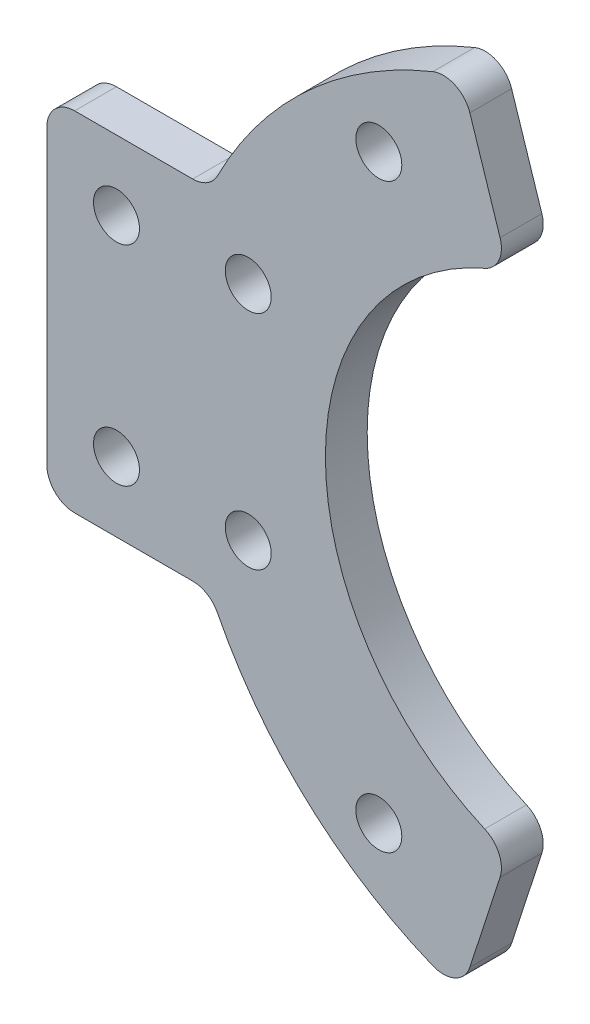
SolidWorks part; units mm, degrees
ref_plane "Front Plane" through (0, 0, 0) normal (0, 0, 1) x (1, 0, 0)
ref_plane "Top Plane" through (0, 0, 0) normal (0, 1, 0) x (1, 0, 0)
ref_plane "Right Plane" through (0, 0, 0) normal (1, 0, 0) x (0, 0, -1)
sketch "Sketch1" plane through (0, 0, 0) normal (0, 0, 1) x (1, 0, 0)
  line L0 (-17.2607, 53.1231) -> (-12.9197, 39.7628)
  line L1 (-12.9197, -39.7628) -> (-17.2607, -53.1231)
  line L2 (-51.6, 0) -> (-68, 0) construction
  line L3 (-68, 15) -> (-68, -15) construction
  line L4 (-57.0526, 25) -> (-74, 25)
  line L5 (-78, 21) -> (-78, -21)
  line L6 (-74, -25) -> (-57.0526, -25)
  arc A0 (-15.1312, -34.8575) -> (-15.1312, 34.8575) centre (0, 0) cw
  arc A1 (-22.5696, -55.5933) -> (-22.5696, 55.5933) centre (0, 0) cw construction
  arc A2 (-12.9197, 39.7628) -> (-15.1312, 34.8575) centre (-16.7239, 38.5267) cw
  arc A3 (-17.2607, 53.1231) -> (-22.5696, 55.5933) centre (-21.065, 51.8871) ccw
  arc A4 (-17.2607, -53.1231) -> (-22.5696, -55.5933) centre (-21.065, -51.8871) cw
  arc A5 (-12.9197, -39.7628) -> (-15.1312, -34.8575) centre (-16.7239, -38.5267) ccw
  circle A6 centre (0, 0) radius 51.6 construction
  circle A7 centre (0, 51.6) radius 3.3 construction
  circle A8 centre (30.3297, 41.7453) radius 3.3 construction
  circle A9 centre (49.0745, 15.9453) radius 3.3 construction
  circle A10 centre (49.0745, -15.9453) radius 3.3 construction
  circle A11 centre (30.3297, -41.7453) radius 3.3 construction
  circle A12 centre (0, -51.6) radius 3.3 construction
  circle A13 centre (-30.3297, -41.7453) radius 3.3
  circle A14 centre (-49.0745, -15.9453) radius 3.3
  circle A15 centre (-49.0745, 15.9453) radius 3.3
  circle A16 centre (-30.3297, 41.7453) radius 3.3
  circle A17 centre (-68, 15) radius 3.3
  circle A18 centre (-68, -15) radius 3.3
  arc A19 (-53.4868, 27.1875) -> (-22.5696, 55.5933) centre (0, 0) cw
  arc A20 (-22.5696, -55.5933) -> (-53.4868, -27.1875) centre (0, 0) cw
  arc A21 (-74, 25) -> (-78, 21) centre (-74, 21) ccw
  arc A22 (-78, -21) -> (-74, -25) centre (-74, -21) ccw
  arc A23 (-53.4868, -27.1875) -> (-57.0526, -25) centre (-57.0526, -29) ccw
  arc A24 (-53.4868, 27.1875) -> (-57.0526, 25) centre (-57.0526, 29) cw
  point P4 (-38, 0)
  point P9 (-60, 0)
  point P10 (-11.7426, 36.1401)
  point P13 (-18.541, 57.0634)
  point P16 (-18.541, -57.0634)
  point P19 (-11.7426, -36.1401)
  point P44 (0, 0)
  point P47 (-68, 0)
  point P52 (-78, 0)
  point P61 (-54.5436, -25)
  point P64 (-54.5436, 25)
  dimension "InnerDiameter" = 38
  dimension "OuterDiameter" = 60
  dimension "D1" = 4
  dimension "ExternalRadius" = 4
  dimension "D4" = 4
  dimension "D5" = 4
  dimension "FlangeHoleDiameter" = 103.2
  dimension "M6ClearanceDiameter" = 6.6
  dimension "D7" = 4
  dimension "D8" = 4
  dimension "D9" = 4
  dimension "D10" = 4
  dimension "StrutHoleSeparation" = 30
  dimension "StrutHoleOffsetRadius" = 68
  dimension "StrutHoleBoundary" = 10
  dimension "D6" = 10
  dimension "D2" = 144
  dimension "ArcAngle" = 144
  dimension "D3" = 10
extrude "Boss-Extrude1" add sketch "Sketch1" along normal blind 6
sketch "Sketch2" plane through (0, 0, 0) normal (0, 0, -1) x (-1, 0, 0)
  arc A0 (53.4868, 27.1875) -> (53.4868, -27.1875) centre (0, 0) cw
  arc A1 (22.5696, -55.5933) -> (53.4868, -27.1875) centre (0, 0) ccw construction
split line "Split Line1"
equation "\"D2@Sketch1\"=\"ArcAngle@Sketch1\""
equation "\"D1@Sketch1\"=\"ExternalRadius@Sketch1\""
equation "\"D5@Sketch1\"=\"ExternalRadius@Sketch1\""
equation "\"D4@Sketch1\"=\"ExternalRadius@Sketch1\""
equation "\"D6@Sketch1\"=\"StrutHoleBoundary@Sketch1\""
equation "\"InnerDiameter@Sketch1\"= 76 / 2"
